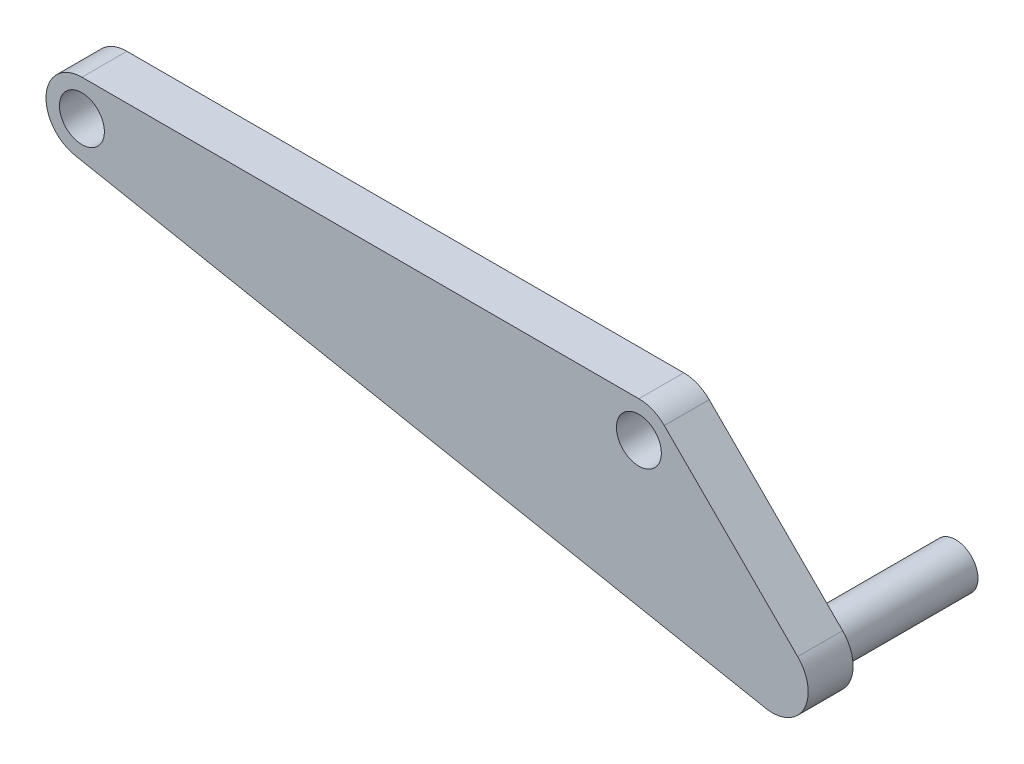
SolidWorks part; units mm, degrees
material "ABS"
ref_plane "Front Plane" through (0, 0, 0) normal (0, 0, 1) x (1, 0, 0)
ref_plane "Top Plane" through (0, 0, 0) normal (0, 1, 0) x (1, 0, 0)
ref_plane "Right Plane" through (0, 0, 0) normal (1, 0, 0) x (0, 0, -1)
sketch "Sketch1" plane through (0, 0, 0) normal (0, 0, 1) x (1, 0, 0)
  line L0 (0, 0) -> (-62, 0)
  line L2 (0, 0) -> (14.8492, -14.8492)
  dimension "D1" = 62
  dimension "D3" = 21
  dimension "D5" = 135
sketch "Sketch2" plane through (0, 0, 0) normal (0, 0, 1) x (1, 0, 0)
  line L0 (-62, 4) -> (0, 4)
  line L1 (2.8284, 2.8284) -> (17.6777, -12.0208)
  line L2 (14.0904, -18.7766) -> (-62.7589, -3.9274)
  circle A0 centre (-62, 0) radius 2.5
  circle A4 centre (0, 0) radius 2.5
  arc A6 (2.8284, 2.8284) -> (0, 4) centre (0, 0) ccw
  arc A7 (14.0904, -18.7766) -> (17.6777, -12.0208) centre (14.8492, -14.8492) ccw
  arc A8 (-62, 4) -> (-62.7589, -3.9274) centre (-62, 0) ccw
  dimension "D1" = 8
  dimension "D2" = 5
  dimension "D3" = 5
  dimension "D7" = 8
  dimension "D8" = 8
extrude "Boss-Extrude1" add sketch "Sketch2" along normal blind 5
sketch "Sketch3" plane through (0, 0, 0) normal (0, 0, -1) x (-1, 0, 0)
  circle A0 centre (-14.8492, -14.8492) radius 2.5
  circle A1 centre (-14.8492, -14.8492) radius 0.5
  dimension "D1" = 5
  dimension "D2" = 1
extrude "Boss-Extrude2" add sketch "Sketch3" along normal blind 15.4
